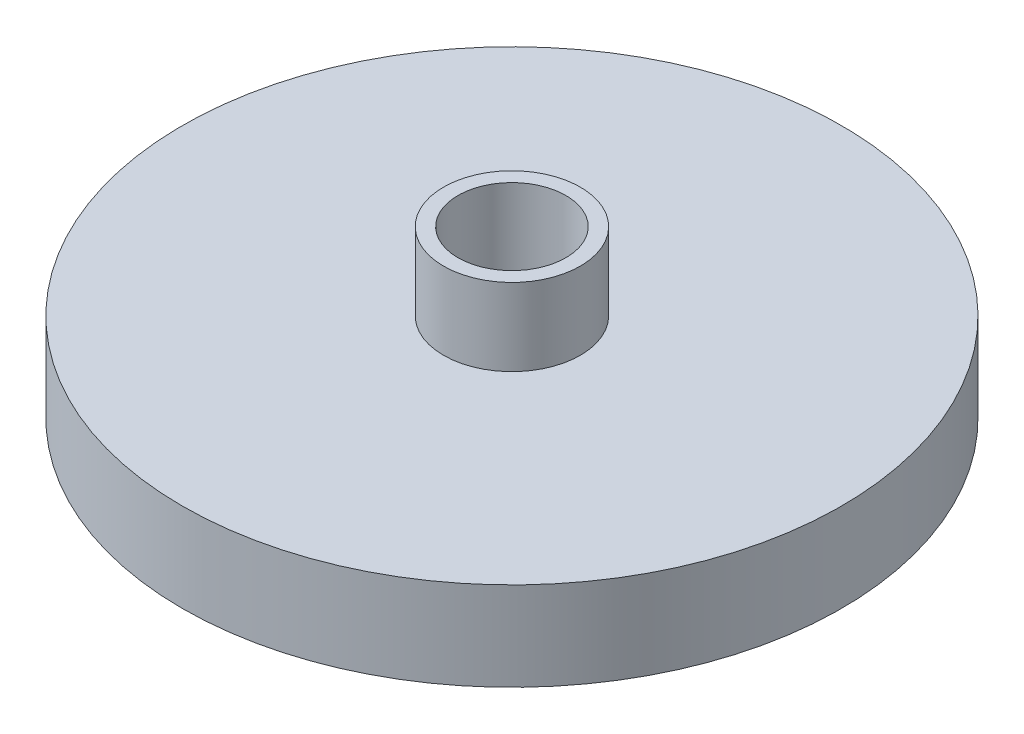
SolidWorks part; units mm, degrees
material "ABS"
ref_plane "Front Plane" through (0, 0, 0) normal (0, 0, 1) x (1, 0, 0)
ref_plane "Top Plane" through (0, 0, 0) normal (0, 1, 0) x (1, 0, 0)
ref_plane "Right Plane" through (0, 0, 0) normal (1, 0, 0) x (0, 0, -1)
sketch "Sketch1" plane through (0, 0, 0) normal (0, 1, 0) x (1, 0, 0)
  circle A0 centre (0, 0) radius 19.3929
  dimension "D1" = 38.7858
extrude "Boss-Extrude1" add sketch "Sketch1" along normal blind 5.22
sketch "Sketch2" plane through (0, 5.22, 0) normal (0, 1, 0) x (1, 0, 0)
  circle A0 centre (0, 0) radius 3.175
  dimension "D1" = 6.35
extrude "Cut-Extrude1" cut sketch "Sketch2" along direction (0, 1, 0) on the side against the normal through all
sketch "Sketch3" plane through (0, 5.22, 0) normal (0, 1, 0) x (1, 0, 0)
  circle A0 centre (0, 0) radius 4.0259
  circle A1 centre (0, 0) radius 3.175 construction
  circle A2 centre (0, 0) radius 3.175
  dimension "D1" = 0.8509
extrude "Boss-Extrude2" add sketch "Sketch3" along normal blind 4.5466
